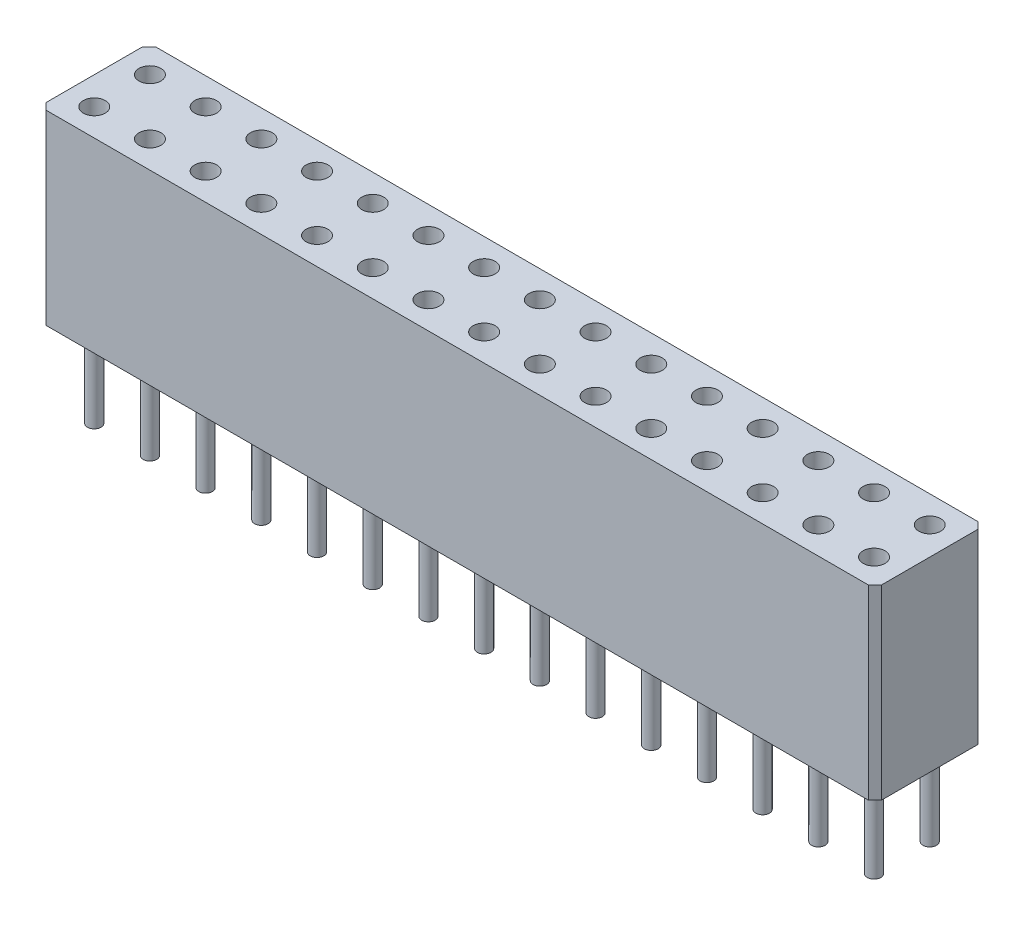
SolidWorks part; units mm, degrees
ref_plane "Спереди" through (0, 0, 0) normal (0, 0, 1) x (1, 0, 0)
ref_plane "Сверху" through (0, 0, 0) normal (0, 1, 0) x (1, 0, 0)
ref_plane "Справа" through (0, 0, 0) normal (1, 0, 0) x (0, 0, -1)
sketch "Эскиз2" plane through (0, 0, 0) normal (0, 1, 0) x (1, 0, 0)
  line L2 (49.4117, 10.0437) -> (74.2117, 10.0437)
  line L3 (36.7117, 10.0437) -> (49.4117, 10.0437)
  line L4 (36.7117, 15.0437) -> (74.2117, 15.0437)
  line L5 (74.5117, 14.7437) -> (74.5117, 10.3437)
  line L8 (74.5117, 14.7437) -> (74.2117, 15.0437)
  line L9 (74.5117, 10.3437) -> (74.2117, 10.0437)
  line L17 (36.4117, 14.7437) -> (36.4117, 10.3437)
  line L18 (36.7117, 10.0437) -> (36.4117, 10.3437)
  line L19 (36.7117, 15.0437) -> (36.4117, 14.7437)
  circle A4 centre (73.2417, 11.2737) radius 0.31
  circle A5 centre (70.7017, 11.2737) radius 0.31
  circle A6 centre (68.1617, 11.2737) radius 0.31
  circle A7 centre (65.6217, 11.2737) radius 0.31
  circle A8 centre (63.0817, 11.2737) radius 0.31
  circle A9 centre (60.5417, 11.2737) radius 0.31
  circle A10 centre (58.0017, 11.2737) radius 0.31
  circle A11 centre (55.4617, 11.2737) radius 0.31
  circle A12 centre (52.9217, 11.2737) radius 0.31
  circle A13 centre (50.3817, 11.2737) radius 0.31
  circle A14 centre (47.8417, 11.2737) radius 0.31
  circle A15 centre (45.3017, 11.2737) radius 0.31
  circle A16 centre (42.7617, 11.2737) radius 0.31
  circle A17 centre (40.2217, 11.2737) radius 0.31
  circle A18 centre (37.6817, 11.2737) radius 0.31
  circle A23 centre (73.2417, 13.8137) radius 0.31
  circle A24 centre (70.7017, 13.8137) radius 0.31
  circle A25 centre (68.1617, 13.8137) radius 0.31
  circle A26 centre (65.6217, 13.8137) radius 0.31
  circle A27 centre (63.0817, 13.8137) radius 0.31
  circle A28 centre (60.5417, 13.8137) radius 0.31
  circle A30 centre (58.0017, 13.8137) radius 0.31
  circle A31 centre (55.4617, 13.8137) radius 0.31
  circle A32 centre (52.9217, 13.8137) radius 0.31
  circle A33 centre (50.3817, 13.8137) radius 0.31
  circle A34 centre (47.8417, 13.8137) radius 0.31
  circle A35 centre (45.3017, 13.8137) radius 0.31
  circle A36 centre (42.7617, 13.8137) radius 0.31
  circle A37 centre (40.2217, 13.8137) radius 0.31
  circle A38 centre (37.6817, 13.8137) radius 0.31
  point P13 (54.5411, 14.8708)
  point P174 (57.0811, 14.8708)
extrude "Бобышка-Вытянуть4" add sketch "Эскиз2" against normal blind 8.5
sketch "Эскиз7" plane through (0, 0, 0) normal (0, 1, 0) x (1, 0, 0)
  circle A0 centre (83.4017, 11.2737) radius 0.5
  circle A1 centre (80.8617, 11.2737) radius 0.5
  circle A2 centre (78.3217, 11.2737) radius 0.5
  circle A3 centre (75.7817, 11.2737) radius 0.5
  circle A4 centre (73.2417, 11.2737) radius 0.5
  circle A5 centre (70.7017, 11.2737) radius 0.5
  circle A6 centre (68.1617, 11.2737) radius 0.5
  circle A7 centre (65.6217, 11.2737) radius 0.5
  circle A8 centre (63.0817, 11.2737) radius 0.5
  circle A9 centre (60.5417, 11.2737) radius 0.5
  circle A10 centre (58.0017, 11.2737) radius 0.5
  circle A11 centre (55.4617, 11.2737) radius 0.5
  circle A12 centre (52.9217, 11.2737) radius 0.5
  circle A13 centre (50.3817, 11.2737) radius 0.5
  circle A14 centre (47.8417, 11.2737) radius 0.5
  circle A15 centre (45.3017, 11.2737) radius 0.5
  circle A16 centre (42.7617, 11.2737) radius 0.5
  circle A17 centre (40.2217, 11.2737) radius 0.5
  circle A18 centre (37.6817, 11.2737) radius 0.5
  circle A19 centre (83.4017, 13.8137) radius 0.5
  circle A20 centre (80.8617, 13.8137) radius 0.5
  circle A21 centre (78.3217, 13.8137) radius 0.5
  circle A22 centre (75.7817, 13.8137) radius 0.5
  circle A23 centre (73.2417, 13.8137) radius 0.5
  circle A24 centre (70.7017, 13.8137) radius 0.5
  circle A25 centre (68.1617, 13.8137) radius 0.5
  circle A26 centre (65.6217, 13.8137) radius 0.5
  circle A27 centre (63.0817, 13.8137) radius 0.5
  circle A28 centre (60.5417, 13.8137) radius 0.5
  circle A29 centre (85.9417, 11.2737) radius 0.5
  circle A58 centre (58.0017, 13.8137) radius 0.5
  circle A59 centre (55.4617, 13.8137) radius 0.5
  circle A60 centre (52.9217, 13.8137) radius 0.5
  circle A61 centre (50.3817, 13.8137) radius 0.5
  circle A62 centre (47.8417, 13.8137) radius 0.5
  circle A63 centre (45.3017, 13.8137) radius 0.5
  circle A64 centre (42.7617, 13.8137) radius 0.5
  circle A65 centre (40.2217, 13.8137) radius 0.5
  circle A66 centre (37.6817, 13.8137) radius 0.5
  circle A67 centre (85.9417, 13.8137) radius 0.5
extrude "Вырез-Вытянуть1" cut sketch "Эскиз7" against normal blind 8
sketch "Эскиз8" plane through (0, -8.5, 0) normal (0, -1, 0) x (1, 0, 0)
  circle A0 centre (37.6817, -11.2737) radius 0.31
  circle A1 centre (40.2217, -11.2737) radius 0.31
  circle A2 centre (42.7617, -11.2737) radius 0.31
  circle A3 centre (45.3017, -11.2737) radius 0.31
  circle A4 centre (47.8417, -11.2737) radius 0.31
  circle A5 centre (50.3817, -11.2737) radius 0.31
  circle A6 centre (52.9217, -11.2737) radius 0.31
  circle A7 centre (55.4617, -11.2737) radius 0.31
  circle A8 centre (58.0017, -11.2737) radius 0.31
  circle A9 centre (60.5417, -11.2737) radius 0.31
  circle A10 centre (63.0817, -11.2737) radius 0.31
  circle A11 centre (65.6217, -11.2737) radius 0.31
  circle A12 centre (68.1617, -11.2737) radius 0.31
  circle A13 centre (70.7017, -11.2737) radius 0.31
  circle A14 centre (73.2417, -11.2737) radius 0.31
  circle A20 centre (40.2217, -13.8137) radius 0.31
  circle A21 centre (42.7617, -13.8137) radius 0.31
  circle A22 centre (45.3017, -13.8137) radius 0.31
  circle A23 centre (47.8417, -13.8137) radius 0.31
  circle A24 centre (50.3817, -13.8137) radius 0.31
  circle A25 centre (52.9217, -13.8137) radius 0.31
  circle A26 centre (55.4617, -13.8137) radius 0.31
  circle A27 centre (58.0017, -13.8137) radius 0.31
  circle A28 centre (60.5417, -13.8137) radius 0.31
  circle A29 centre (63.0817, -13.8137) radius 0.31
  circle A30 centre (65.6217, -13.8137) radius 0.31
  circle A31 centre (68.1617, -13.8137) radius 0.31
  circle A32 centre (70.7017, -13.8137) radius 0.31
  circle A33 centre (73.2417, -13.8137) radius 0.31
  circle A39 centre (37.6817, -13.8137) radius 0.31
  circle A40 centre (75.7817, -11.2737) radius 0.31 [skipped]
  circle A41 centre (75.7817, -13.8137) radius 0.31 [skipped]
  circle A42 centre (78.3217, -13.8137) radius 0.31 [skipped]
  circle A43 centre (80.8617, -13.8137) radius 0.31 [skipped]
  circle A44 centre (80.8617, -11.2737) radius 0.31 [skipped]
  circle A45 centre (78.3217, -11.2737) radius 0.31 [skipped]
  circle A46 centre (83.4017, -11.2737) radius 0.31 [skipped]
  circle A47 centre (83.4017, -13.8137) radius 0.31 [skipped]
  circle A48 centre (85.9417, -13.8137) radius 0.31 [skipped]
  circle A49 centre (85.9417, -11.2737) radius 0.31 [skipped]
  point P3 (0, 0)
  point P4 (0, 0)
  point P5 (0, 0)
  point P34 (0, 0)
  point P35 (0, 0)
  point P36 (0, 0)
  point P38 (0, 0)
  point P72 (0, 0)
  dimension "D1" = 20
  dimension "D2" = 2
extrude "Бобышка-Вытянуть5" add sketch "Эскиз8" along normal blind 4 separate body
